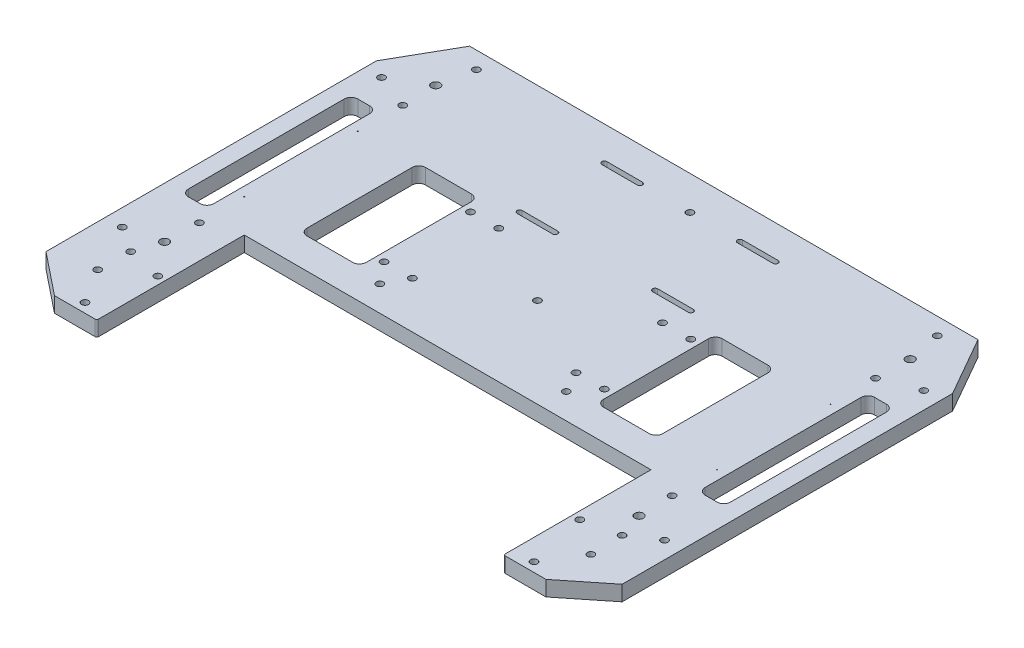
SolidWorks part; units mm, degrees
ref_plane "Plan de face" through (0, 0, 0) normal (0, 0, 1) x (1, 0, 0)
ref_plane "Plan de dessus" through (0, 0, 0) normal (0, 1, 0) x (1, 0, 0)
ref_plane "Plan de droite" through (0, 0, 0) normal (1, 0, 0) x (0, 0, -1)
sketch "Esquisse3" plane through (0, 0, 0) normal (0, 1, 0) x (1, 0, 0)
  line L0 (-281.7629, 0) -> (308.2067, 0) construction
  line L1 (0, 166.4902) -> (0, -269.1166) construction
  line L4 (-160, -46) -> (-160, 46)
  line L5 (-156, 50) -> (-149, 50)
  line L6 (-145, 46) -> (-145, -46)
  line L7 (-105, 0) -> (-105, 31)
  line L8 (-101, 35) -> (-74, 35)
  line L9 (-70, 31) -> (-70, -31)
  line L11 (-105, 0) -> (-105, -31)
  line L12 (-101, -35) -> (-74, -35)
  line L13 (-156, -50) -> (-149, -50)
  line L17 (156, 50) -> (149, 50)
  line L18 (156, -50) -> (149, -50)
  line L19 (145, 46) -> (145, -46)
  line L20 (160, -46) -> (160, 46)
  line L21 (105, 0) -> (105, 31)
  line L22 (101, -35) -> (74, -35)
  line L23 (105, 0) -> (105, -31)
  line L24 (70, 31) -> (70, -31)
  line L25 (101, 35) -> (74, 35)
  line L26 (150, 110) -> (-150, 110)
  line L34 (-170, 75) -> (-150, 110)
  line L35 (170, 75) -> (150, 110)
  line L38 (-170, 75) -> (-170, 0)
  line L39 (-170, 0) -> (-170, -120)
  line L40 (170, -120) -> (170, 0)
  line L41 (170, 0) -> (170, 75)
  line L43 (-170, -120) -> (-145, -140)
  line L44 (145, -140) -> (170, -120)
  line L45 (-145, -140) -> (-120, -140)
  line L46 (-120, -140) -> (-120, -53)
  line L47 (-120, -53) -> (120, -53)
  line L48 (120, -53) -> (120, -140)
  line L49 (120, -140) -> (145, -140)
  line L50 (-170, 75) -> (170, 75) construction
  line L51 (-170, 0) -> (-220, 0) construction
  line L52 (-220, 0) -> (-170, 75) construction
  line L53 (-220, 0) -> (-170, -120) construction
  line L54 (-130, -140) -> (-130, -220) construction
  line L55 (-130, -220) -> (130, -220) construction
  line L56 (130, -140) -> (130, -220) construction
  line L57 (-170, -120) -> (-130, -220) construction
  line L58 (-170, 0) -> (-200, 0) construction
  line L60 (-150, 90) -> (-130, 90) construction
  line L61 (-150, 90) -> (-150, 70) construction
  line L62 (-150, 70) -> (-130, 70) construction
  line L63 (-130, 90) -> (-130, 70) construction
  line L64 (-150, 90) -> (-130, 70) construction
  line L65 (-150, 70) -> (-130, 90) construction
  arc A0 (-149, 50) -> (-145, 46) centre (-149, 46) cw
  arc A1 (-74, 35) -> (-70, 31) centre (-74, 31) cw
  arc A2 (-105, 31) -> (-101, 35) centre (-101, 31) cw
  arc A3 (-160, 46) -> (-156, 50) centre (-156, 46) cw
  arc A4 (-105, -31) -> (-101, -35) centre (-101, -31) ccw
  arc A5 (-74, -35) -> (-70, -31) centre (-74, -31) ccw
  arc A6 (-160, -46) -> (-156, -50) centre (-156, -46) ccw
  arc A7 (-149, -50) -> (-145, -46) centre (-149, -46) ccw
  arc A8 (149, 50) -> (145, 46) centre (149, 46) ccw
  arc A9 (160, 46) -> (156, 50) centre (156, 46) ccw
  arc A10 (149, -50) -> (145, -46) centre (149, -46) cw
  arc A11 (160, -46) -> (156, -50) centre (156, -46) cw
  arc A12 (74, -35) -> (70, -31) centre (74, -31) cw
  arc A13 (105, -31) -> (101, -35) centre (101, -31) cw
  arc A14 (105, 31) -> (101, 35) centre (101, 31) ccw
  arc A15 (74, 35) -> (70, 31) centre (74, 31) ccw
  circle A16 centre (-140, 80) radius 2.55
  circle A17 centre (-140, -80) radius 2.55
  circle A18 centre (140, -80) radius 2.55
  circle A19 centre (140, 80) radius 2.55
  circle A20 centre (0, 0) radius 200 construction
  circle A21 centre (0, 0) radius 185.809 construction
  point P6 (-170, 110)
  point P16 (-105, 15.5)
  point P19 (-145, 50)
  point P22 (-70, 35)
  point P25 (-105, 35)
  point P28 (-160, 50)
  point P32 (-70, 0)
  point P37 (-105, -35)
  point P38 (-70, -35)
  point P40 (-145, 0)
  point P41 (-160, 0)
  point P45 (-160, -50)
  point P46 (-145, -50)
  point P47 (0, 110)
  point P48 (-170, 0)
  point P51 (0, -110)
  point P64 (145, -50)
  point P65 (160, -50)
  point P75 (70, -35)
  point P76 (105, -35)
  point P81 (105, 35)
  point P82 (70, 35)
  point P83 (0, -269.1166)
  point P85 (0, 110)
  point P94 (-170, 0)
  point P97 (170, 0)
  point P100 (0, -130)
  dimension "D7" = 4
  dimension "D10" = 5.1
  dimension "D32" = 30
  dimension "D33" = 400
  dimension "D34" = 371.6181
  dimension "D2" = 300
  dimension "D3" = 35
  dimension "D4" = 15
  dimension "D5" = 70
  dimension "D6" = 40
  dimension "D14" = 25
  dimension "D13" = 110
  dimension "D8" = 35
  dimension "D9" = 50
  dimension "D11" = 240
  dimension "D12" = 340
  dimension "D15" = 120
  dimension "D16" = 75
  dimension "D17" = 140
  dimension "D18" = 80
  dimension "D19" = 87
  dimension "D20" = 140
  dimension "D21" = 150
  dimension "D22" = 32.0156
  dimension "D23" = 40.3113
  dimension "D24" = 120
  dimension "D25" = 50
  dimension "D26" = 130
  dimension "D27" = 90.1388
  dimension "D28" = 80
  dimension "D29" = 10
  dimension "D30" = 107.7033
  dimension "D31" = 130
  dimension "D35" = 20
  dimension "D36" = 250
extrude "structure" add sketch "Esquisse3" against normal blind 9
sketch "Esquisse4" plane through (0, 0, 0) normal (0, 1, 0) x (1, 0, 0)
  line L0 (-232.6304, 0) -> (230.9735, 0) construction
  line L1 (0, 112.1729) -> (0, -129.4048) construction
  line L3 (-145, -46) -> (-145, 46) construction
  line L12 (-150, 110) -> (-170, 75)
  line L13 (-170, 75) -> (-170, -120)
  line L14 (-170, -120) -> (-145, -140)
  line L15 (-120, -53) -> (120, -53)
  line L16 (145, -140) -> (170, -120)
  line L17 (170, -120) -> (170, 75)
  line L18 (170, 75) -> (150, 110)
  line L19 (150, 110) -> (-150, 110)
  line L20 (-150, 110) -> (-170, 75)
  line L21 (-170, 75) -> (-170, -120)
  line L22 (-170, -120) -> (-145, -140)
  line L24 (145, -140) -> (170, -120)
  line L25 (170, -120) -> (170, 75)
  line L26 (170, 75) -> (150, 110)
  line L27 (150, 110) -> (-150, 110)
  line L32 (-120, -53) -> (120, -53)
  line L33 (120, -53) -> (120, -140)
  line L34 (120, -53) -> (120, -140)
  line L35 (120, -140) -> (145, -140)
  line L36 (120, -140) -> (145, -140)
  line L37 (-145, -140) -> (-120, -140)
  line L38 (-145, -140) -> (-120, -140)
  line L39 (-120, -140) -> (-120, -53)
  line L40 (-120, -140) -> (-120, -53)
  circle A0 centre (-139.5, 33.5) radius 0.25
  circle A2 centre (-139.5, -33.5) radius 0.25
  circle A3 centre (139.5, -33.5) radius 0.25
  circle A4 centre (139.5, 33.5) radius 0.25
  dimension "D1" = 0.5
  dimension "D2" = 0
  dimension "D3" = 33.5
  dimension "D4" = 5.5
extrude "encoches_tiges" cut sketch "Esquisse4" against normal blind 5 contours A3 | A4 | A2 | A0
sketch "Esquisse5" plane through (0, 0, 0) normal (0, 1, 0) x (1, 0, 0)
  line L0 (-244.8916, 0) -> (242.9033, 0) construction
  line L1 (0, 111.8416) -> (0, -134.3756) construction
  line L3 (-145, -46) -> (-145, 46) construction
  line L12 (-150, 110) -> (-170, 75)
  line L13 (-170, 75) -> (-170, -120)
  line L14 (-170, -120) -> (-145, -140)
  line L15 (-120, -53) -> (120, -53)
  line L16 (145, -140) -> (170, -120)
  line L17 (170, -120) -> (170, 75)
  line L18 (170, 75) -> (150, 110)
  line L19 (150, 110) -> (-150, 110)
  line L20 (-150, 110) -> (-170, 75)
  line L21 (-170, 75) -> (-170, -120)
  line L22 (-170, -120) -> (-145, -140)
  line L24 (145, -140) -> (170, -120)
  line L25 (170, -120) -> (170, 75)
  line L26 (170, 75) -> (150, 110)
  line L27 (150, 110) -> (-150, 110)
  line L32 (-120, -53) -> (120, -53)
  line L33 (120, -53) -> (120, -140)
  line L34 (120, -53) -> (120, -140)
  line L35 (120, -140) -> (145, -140)
  line L36 (120, -140) -> (145, -140)
  line L37 (-145, -140) -> (-120, -140)
  line L38 (-145, -140) -> (-120, -140)
  line L39 (-120, -140) -> (-120, -53)
  line L40 (-120, -140) -> (-120, -53)
  circle A0 centre (-139.5, 60) radius 2.05
  circle A1 centre (-139.5, -60) radius 2.05
  circle A2 centre (139.5, -60) radius 2.05
  circle A3 centre (139.5, 60) radius 2.05
  dimension "D3" = 4.1
  dimension "D1" = 60
  dimension "D2" = 0
  dimension "D4" = 5.5
extrude "encodeurs" cut sketch "Esquisse5" against normal through all contours A1 | A0 | A3 | A2
sketch "Esquisse6" plane through (0, 0, 0) normal (0, 1, 0) x (1, 0, 0)
  line L0 (0, 109.8533) -> (0, -117.4751) construction
  line L1 (-179.2779, 0) -> (195.847, 0) construction
  line L2 (-98.5767, 25.5) -> (7.2216, 25.5) construction
  line L4 (-70, -31) -> (-70, 31) construction
  line L12 (-150, 110) -> (-170, 75)
  line L13 (-170, 75) -> (-170, -120)
  line L14 (-170, -120) -> (-145, -140)
  line L15 (-120, -53) -> (120, -53)
  line L16 (145, -140) -> (170, -120)
  line L17 (170, -120) -> (170, 75)
  line L18 (170, 75) -> (150, 110)
  line L19 (150, 110) -> (-150, 110)
  line L20 (-150, 110) -> (-170, 75)
  line L21 (-170, 75) -> (-170, -120)
  line L22 (-170, -120) -> (-145, -140)
  line L24 (145, -140) -> (170, -120)
  line L25 (170, -120) -> (170, 75)
  line L26 (170, 75) -> (150, 110)
  line L27 (150, 110) -> (-150, 110)
  line L33 (-120, -53) -> (120, -53)
  line L34 (120, -53) -> (120, -140)
  line L35 (120, -53) -> (120, -140)
  line L36 (120, -140) -> (145, -140)
  line L37 (120, -140) -> (145, -140)
  line L38 (-145, -140) -> (-120, -140)
  line L39 (-145, -140) -> (-120, -140)
  line L40 (-120, -140) -> (-120, -53)
  line L41 (-120, -140) -> (-120, -53)
  circle A0 centre (-65, 25.5) radius 2.05
  circle A1 centre (-48.3, 25.5) radius 2.05
  circle A2 centre (-48.3, -25.5) radius 2.05
  circle A3 centre (-65, -25.5) radius 2.05
  circle A4 centre (65, -25.5) radius 2.05
  circle A5 centre (48.3, -25.5) radius 2.05
  circle A6 centre (48.3, 25.5) radius 2.05
  circle A7 centre (65, 25.5) radius 2.05
  dimension "D1" = 4.1
  dimension "D2" = 4.1
  dimension "D3" = 16.7
  dimension "D4" = 25.5
  dimension "D5" = 0
  dimension "D6" = 5
extrude "moteurs" cut sketch "Esquisse6" against normal through all both and the other way through all contours A0 | A1 | A3 | A5 | A4 | A2 | A6 | A7
sketch "Esquisse7" plane through (0, 0, 0) normal (0, 1, 0) x (1, 0, 0)
  line L0 (-174.1619, -95) -> (241.5194, -95) construction
  line L2 (0, -145.9077) -> (0, 135.7674) construction
  line L3 (-194.9191, 0) -> (209.9418, 0) construction
  circle A0 centre (0, 90) radius 2.05
  circle A1 centre (0, -90) radius 2.05 construction
  circle A2 centre (0, 0) radius 2.05
  circle A3 centre (-145, -95) radius 2.05
  circle A4 centre (145, -95) radius 2.05
  dimension "D1" = 4.1
  dimension "D3" = 4.1
  dimension "D5" = 145
  dimension "D2" = 90
  dimension "D4" = 95
extrude "patins" cut sketch "Esquisse7" against normal through all
sketch "Esquisse8" plane through (0, 0, 0) normal (0, 1, 0) x (1, 0, 0)
  line L0 (0, 136.7319) -> (0, -163.5964) construction
  line L13 (-120, -53) -> (120, -53)
  line L14 (-120, -53) -> (120, -53)
  line L15 (120, -53) -> (120, -140)
  line L16 (120, -53) -> (120, -140)
  line L17 (120, -140) -> (145, -140)
  line L18 (120, -140) -> (145, -140)
  line L19 (145, -140) -> (170, -120)
  line L20 (145, -140) -> (170, -120)
  line L21 (170, -120) -> (170, 75)
  line L22 (170, -120) -> (170, 75)
  line L23 (170, 75) -> (150, 110)
  line L24 (170, 75) -> (150, 110)
  line L37 (150, 110) -> (-150, 110)
  line L38 (150, 110) -> (-150, 110)
  line L39 (-150, 110) -> (-170, 75)
  line L40 (-150, 110) -> (-170, 75)
  line L41 (-170, 75) -> (-170, -120)
  line L42 (-170, 75) -> (-170, -120)
  line L43 (-170, -120) -> (-145, -140)
  line L44 (-170, -120) -> (-145, -140)
  line L45 (-145, -140) -> (-120, -140)
  line L46 (-145, -140) -> (-120, -140)
  line L47 (-120, -140) -> (-120, -53)
  line L48 (-120, -140) -> (-120, -53)
  circle A0 centre (-132.5, -134.5) radius 2.05
  circle A1 centre (-124.5, -99.5) radius 2.05
  circle A2 centre (132.5, -134.5) radius 2.05
  circle A3 centre (124.5, -99.5) radius 2.05
  circle A4 centre (-145.5, -114) radius 2.05
  circle A5 centre (145.5, -114) radius 2.05
  dimension "D2" = 4.1
  dimension "D7" = 40.5
  dimension "D1" = 0
  dimension "D3" = 4.5
  dimension "D4" = 26
  dimension "D5" = 5.5
  dimension "D6" = 25.5
  dimension "D8" = 12.5
extrude "actionneurs" cut sketch "Esquisse8" against normal through all contours A1 | A0 | A3 | A2 | A4 | A5
fillet "Congé1" radius 1 2 edges at (120, -4.5, 140) (-120, -4.5, 140)
sketch "Esquisse9" plane through (0, 0, 0) normal (0, 1, 0) x (1, 0, 0)
  line L0 (-40, 126.0313) -> (-40, 26.6007) construction
  line L1 (-55.866, 65) -> (23.4115, 65) construction
  line L2 (-50.5, 90) -> (-29.5, 90) construction
  line L3 (-50.5, 91.5) -> (-29.5, 91.5)
  line L4 (-50.5, 88.5) -> (-29.5, 88.5)
  line L5 (-50.5, 40) -> (-29.5, 40) construction
  line L6 (-50.5, 38.5) -> (-29.5, 38.5)
  line L7 (-50.5, 41.5) -> (-29.5, 41.5)
  line L8 (0, 0) -> (0, 125.8879) construction
  line L9 (50.5, 40) -> (29.5, 40) construction
  line L10 (50.5, 38.5) -> (29.5, 38.5)
  line L11 (50.5, 41.5) -> (29.5, 41.5)
  line L12 (120, -53) -> (120, -139)
  line L13 (121, -140) -> (145, -140)
  line L14 (145, -140) -> (170, -120)
  line L15 (170, -120) -> (170, 75)
  line L16 (170, 75) -> (150, 110)
  line L17 (150, 110) -> (-150, 110)
  line L18 (-150, 110) -> (-170, 75)
  line L19 (-170, 75) -> (-170, -120)
  line L20 (-170, -120) -> (-145, -140)
  line L21 (-145, -140) -> (-121, -140)
  line L22 (-120, -139) -> (-120, -53)
  line L23 (-120, -53) -> (120, -53)
  line L24 (120, -53) -> (120, -139)
  line L25 (121, -140) -> (145, -140)
  line L26 (145, -140) -> (170, -120)
  line L27 (170, -120) -> (170, 75)
  line L28 (170, 75) -> (150, 110)
  line L29 (150, 110) -> (-150, 110)
  line L30 (-150, 110) -> (-170, 75)
  line L31 (-170, 75) -> (-170, -120)
  line L32 (-170, -120) -> (-145, -140)
  line L33 (-145, -140) -> (-121, -140)
  line L34 (-120, -139) -> (-120, -53)
  line L35 (-120, -53) -> (120, -53)
  line L36 (50.5, 90) -> (29.5, 90) construction
  line L37 (50.5, 91.5) -> (29.5, 91.5)
  line L38 (50.5, 88.5) -> (29.5, 88.5)
  line L39 (-70, 90) -> (-70, 54.007) construction
  arc A0 (-50.5, 91.5) -> (-50.5, 88.5) centre (-50.5, 90) ccw
  arc A1 (-29.5, 88.5) -> (-29.5, 91.5) centre (-29.5, 90) ccw
  arc A2 (120, -139) -> (121, -140) centre (121, -139) ccw
  arc A3 (-121, -140) -> (-120, -139) centre (-121, -139) ccw
  arc A4 (120, -139) -> (121, -140) centre (121, -139) ccw
  arc A5 (-121, -140) -> (-120, -139) centre (-121, -139) ccw
  arc A6 (-50.5, 38.5) -> (-50.5, 41.5) centre (-50.5, 40) cw
  arc A7 (-29.5, 41.5) -> (-29.5, 38.5) centre (-29.5, 40) cw
  arc A8 (50.5, 38.5) -> (50.5, 41.5) centre (50.5, 40) ccw
  arc A9 (29.5, 41.5) -> (29.5, 38.5) centre (29.5, 40) ccw
  arc A10 (50.5, 91.5) -> (50.5, 88.5) centre (50.5, 90) cw
  arc A11 (29.5, 88.5) -> (29.5, 91.5) centre (29.5, 90) cw
  point P17 (-40, 90)
  point P29 (-40, 40)
  point P39 (40, 40)
  point P46 (40, 90)
  dimension "D2" = 3
  dimension "D3" = 21
  dimension "D4" = 25
  dimension "D5" = 65
  dimension "D6" = 40
  dimension "D7" = 70
  dimension "D1" = 0
extrude "batterie" cut sketch "Esquisse9" against normal blind 30 contours A11 L38 A10 L37 | L4 A1 L3 A0 | L6 A7 L7 A6 | L10 A9 L11 A8
sketch "Esquisse10" plane through (0, 0, 0) normal (0, 1, 0) x (1, 0, 0)
  line L0 (0, 115.28) -> (0, -139) construction
  line L12 (120, -53) -> (120, -139)
  line L13 (121, -140) -> (145, -140)
  line L14 (145, -140) -> (170, -120)
  line L15 (170, -120) -> (170, 75)
  line L16 (170, 75) -> (150, 110)
  line L17 (150, 110) -> (-150, 110)
  line L18 (-150, 110) -> (-170, 75)
  line L19 (-170, 75) -> (-170, -120)
  line L20 (-170, -120) -> (-145, -140)
  line L21 (-145, -140) -> (-121, -140)
  line L22 (-120, -139) -> (-120, -53)
  line L23 (-120, -53) -> (120, -53)
  line L24 (120, -53) -> (120, -139)
  line L25 (121, -140) -> (145, -140)
  line L26 (145, -140) -> (170, -120)
  line L27 (170, -120) -> (170, 75)
  line L28 (170, 75) -> (150, 110)
  line L29 (150, 110) -> (-150, 110)
  line L30 (-150, 110) -> (-170, 75)
  line L31 (-170, 75) -> (-170, -120)
  line L32 (-170, -120) -> (-145, -140)
  line L33 (-145, -140) -> (-121, -140)
  line L34 (-120, -139) -> (-120, -53)
  line L35 (-120, -53) -> (120, -53)
  circle A0 centre (-136, 100) radius 2.05
  circle A1 centre (-160, 68) radius 2.05
  arc A2 (120, -139) -> (121, -140) centre (121, -139) ccw
  arc A3 (-121, -140) -> (-120, -139) centre (-121, -139) ccw
  arc A4 (120, -139) -> (121, -140) centre (121, -139) ccw
  arc A5 (-121, -140) -> (-120, -139) centre (-121, -139) ccw
  circle A6 centre (-160, -85) radius 2.05
  circle A7 centre (160, -85) radius 2.05
  circle A8 centre (160, 68) radius 2.05
  circle A9 centre (136, 100) radius 2.05
  circle A10 centre (-140, 80) radius 2.55 construction
  circle A11 centre (-140, 80) radius 2.55
  circle A12 centre (-140, -80) radius 2.55 construction
  circle A13 centre (-140, -80) radius 2.55
  dimension "D2" = 4.1
  dimension "D3" = 20
  dimension "D4" = 20
  dimension "D5" = 12
  dimension "D6" = 4
  dimension "D7" = 20
  dimension "D8" = 5
  dimension "D1" = 0
extrude "Enlèv. mat.-Extru.1" cut sketch "Esquisse10" against normal blind 10 flip side to cut
sketch "Esquisse11" plane through (0, 0, 0) normal (0, 1, 0) x (1, 0, 0)
  line L0 (0, 110) -> (0, -53) construction
  line L12 (120, -53) -> (120, -139)
  line L13 (121, -140) -> (145, -140)
  line L14 (145, -140) -> (170, -120)
  line L15 (170, -120) -> (170, 75)
  line L16 (170, 75) -> (150, 110)
  line L17 (150, 110) -> (-150, 110)
  line L18 (-150, 110) -> (-170, 75)
  line L19 (-170, 75) -> (-170, -120)
  line L20 (-170, -120) -> (-145, -140)
  line L21 (-145, -140) -> (-121, -140)
  line L22 (-120, -139) -> (-120, -53)
  line L23 (-120, -53) -> (120, -53)
  line L24 (120, -53) -> (120, -139)
  line L25 (121, -140) -> (145, -140)
  line L26 (145, -140) -> (170, -120)
  line L27 (170, -120) -> (170, 75)
  line L28 (170, 75) -> (150, 110)
  line L29 (150, 110) -> (-150, 110)
  line L30 (-150, 110) -> (-170, 75)
  line L31 (-170, 75) -> (-170, -120)
  line L32 (-170, -120) -> (-145, -140)
  line L33 (-145, -140) -> (-121, -140)
  line L34 (-120, -139) -> (-120, -53)
  line L35 (-120, -53) -> (120, -53)
  circle A0 centre (-55, -38) radius 2.05
  circle A1 centre (55, -38) radius 2.05
  arc A2 (120, -139) -> (121, -140) centre (121, -139) ccw
  arc A3 (-121, -140) -> (-120, -139) centre (-121, -139) ccw
  arc A4 (120, -139) -> (121, -140) centre (121, -139) ccw
  arc A5 (-121, -140) -> (-120, -139) centre (-121, -139) ccw
  dimension "D2" = 4.1
  dimension "D3" = 55
  dimension "D4" = 15
  dimension "D1" = 0
extrude "Enlèv. mat.-Extru.2" cut sketch "Esquisse11" against normal blind 10 flip side to cut
